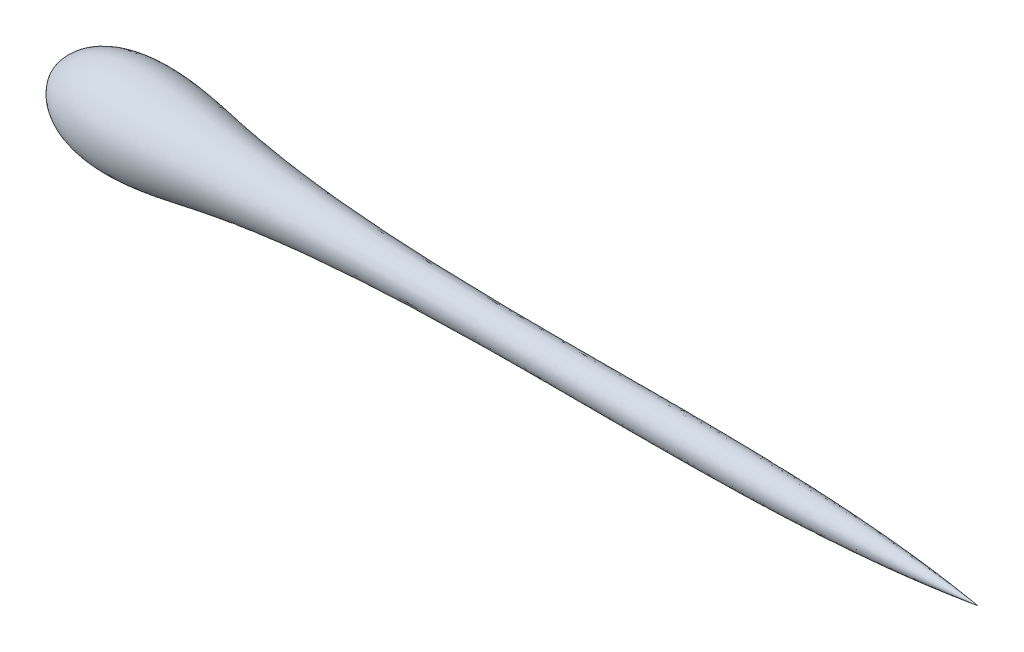
SolidWorks part; units mm, degrees
ref_plane "前视基准面" through (0, 0, 0) normal (0, 0, 1) x (1, 0, 0)
ref_plane "上视基准面" through (0, 0, 0) normal (0, 1, 0) x (1, 0, 0)
ref_plane "右视基准面" through (0, 0, 0) normal (1, 0, 0) x (0, 0, -1)
sketch "草图1" plane through (0, 0, 0) normal (0, 0, 1) x (1, 0, 0)
  line L0 (0, 0) -> (1000, 0)
  spline S0 degree 3 poles (0, 0) (13.0489, 40.9649) (87.3348, 54.2645) (203.1146, 30.8097) (338.1569, 19.4118) (515.9629, 16.5214) (735.3718, 18.6312) (903.034, 12.95) (1000, 0) knots 0 0 0 0 0.112572 0.18839 0.354933 0.506692 0.712749 1 1 1 1
  point P3 (209.0361, 60.2447)
  point P4 (309.0396, 34.5295)
  point P6 (0, 0)
  point P8 (271.8955, 45.9585)
  point P10 (215.703, 68.8164)
  point P12 (19.5056, 28.815)
  point P14 (481.4267, 37.3867)
  point P16 (598.5737, 25.0054)
  point P18 (824.296, 14.5288)
  point P19 (652.8613, 25.9578)
  point P20 (516.666, 25.9578)
  point P21 (497.6177, 17.386)
  point P22 (0, 0)
  point P23 (0, 0)
  point P24 (197.5867, 37.5658)
  point P25 (342.9129, 21.024)
  point P26 (674.3421, 22.4247)
  point P27 (121.0452, 50.05)
  point P28 (853.1264, 13.142)
  point P29 (707.7328, 17.0929)
  point P30 (123.0362, 50.3787)
  point P31 (173.9103, 37.6864)
  point P32 (97.2453, 47.6652)
revolve "旋转1" add sketch "草图1" angle 360 about L0
